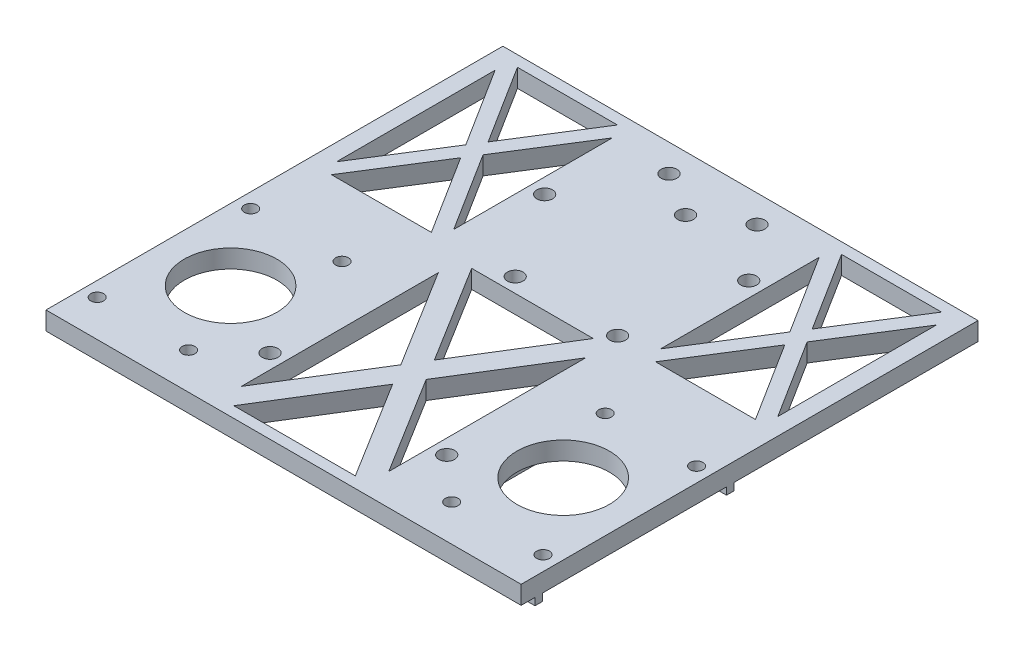
SolidWorks part; units mm, degrees
ref_plane "Front Plane" through (0, 0, 0) normal (0, 0, 1) x (1, 0, 0)
ref_plane "Top Plane" through (0, 0, 0) normal (0, 1, 0) x (1, 0, 0)
ref_plane "Right Plane" through (0, 0, 0) normal (1, 0, 0) x (0, 0, -1)
sketch "Sketch1" plane through (0, 0, 0) normal (0, 1, 0) x (1, 0, 0)
  line L1 (-65, 62.5) -> (65, 62.5)
  line L2 (-65, 62.5) -> (-65, -62.5)
  line L3 (-65, -62.5) -> (65, -62.5)
  line L4 (65, 62.5) -> (65, -62.5)
  line L5 (-65, 62.5) -> (65, -62.5) construction
  line L6 (-65, -62.5) -> (65, 62.5) construction
  point P0 (0, 0)
  dimension "D1" = 130
  dimension "D2" = 125
extrude "Boss-Extrude1" add sketch "Sketch1" along normal blind 5
sketch "Sketch2" plane through (0, 5, 0) normal (0, 1, 0) x (1, 0, 0)
  line L1 (-65, -62.5) -> (65, -62.5) construction
  line L2 (-65, 62.5) -> (-65, -62.5) construction
  circle A0 centre (-61, -52.5) radius 1.75
  circle A1 centre (-36, -52.5) radius 1.75
  circle A2 centre (-36, -10.5) radius 1.75
  circle A3 centre (-61, -10.5) radius 1.75
  circle A4 centre (-45.5, -31.5) radius 12.65
  dimension "D2" = 25.3
  dimension "D7" = 3.5
  dimension "D8" = 3.5
  dimension "D9" = 3.5
  dimension "D10" = 3.5
  dimension "D1" = 19.5
  dimension "D3" = 31
  dimension "D4" = 4
  dimension "D5" = 10
  dimension "D6" = 10
  dimension "D11" = 4
  dimension "D12" = 42
  dimension "D13" = 42
  dimension "D14" = 25
  dimension "D15" = 25
extrude "Cut-Extrude1" cut sketch "Sketch2" against normal blind 10
ref_plane "Plane1" through (0, 0, 0) normal (-1, 0, 0) x (0, 0, 1)
ref_plane "Plane2" through (0, 0, 0) normal (0, 0, 1) x (1, 0, 0)
mirror "Mirror3" about plane through (0, 0, 0) normal (-1, 0, 0) of "Cut-Extrude1"
sketch "Sketch3" plane through (0, 5, 0) normal (0, 1, 0) x (1, 0, 0)
  line L0 (-65, -62.5) -> (65, -62.5) construction
  line L1 (-65, 62.5) -> (-65, -62.5) construction
  line L2 (65, -62.5) -> (65, 62.5) construction
  line L3 (65, 62.5) -> (-65, 62.5) construction
  circle A0 centre (-24.17, -42.03) radius 2.15
  circle A1 centre (24.17, -42.03) radius 2.15
  circle A2 centre (-8.73, 9.6) radius 2.15
  circle A3 centre (19.29, 9.6) radius 2.15
  circle A4 centre (-24.17, 33.11) radius 2.15
  circle A5 centre (24.17, 40.6) radius 2.15
  dimension "D1" = 4.3
  dimension "D6" = 4.3
  dimension "D7" = 4.3
  dimension "D10" = 4.3
  dimension "D11" = 4.3
  dimension "D12" = 4.3
  dimension "D2" = 20.47
  dimension "D3" = 40.83
  dimension "D4" = 20.47
  dimension "D5" = 40.83
  dimension "D8" = 72.1
  dimension "D9" = 56.27
  dimension "D13" = 45.71
  dimension "D14" = 72.1
  dimension "D15" = 29.39
  dimension "D16" = 21.9
  dimension "D17" = 40.83
extrude "Cut-Extrude2" cut sketch "Sketch3" against normal blind 10
sketch "Sketch4" plane through (0, 5, 0) normal (0, 1, 0) x (1, 0, 0)
  line L0 (0, 62.5) -> (0, 47.5) construction
  line L1 (65, 62.5) -> (-65, 62.5) construction
  line L2 (-12.0498, 55) -> (12.0498, 55) construction
  circle A0 centre (0, 47.5) radius 2.15
  circle A1 centre (12.0498, 55) radius 2.15
  circle A2 centre (-12.0498, 55) radius 2.15
  point P9 (0, 55)
  dimension "D2" = 4.3
  dimension "D3" = 4.3
  dimension "D4" = 4.3
  dimension "D1" = 15
  dimension "D5" = 24.0996
extrude "Cut-Extrude3" cut sketch "Sketch4" against normal blind 10
sketch "Sketch5" plane through (0, 0, 0) normal (0, -1, 0) x (1, 0, 0)
  line L0 (-58.15, 31.5) -> (-65, 31.5) construction
  line L1 (-65, -62.5) -> (-65, 62.5) construction
  line L2 (-65, 56.7) -> (-65, 6.3)
  line L3 (-65, 56.7) -> (-31.6, 56.7)
  line L4 (-31.6, 56.7) -> (-31.6, 6.3)
  line L5 (-31.6, 6.3) -> (-65, 6.3)
  line L6 (-65, 58.7) -> (-29.6, 58.7)
  line L7 (-29.6, 58.7) -> (-29.6, 4.3)
  line L8 (-29.6, 4.3) -> (-65, 4.3)
  line L9 (-65, 4.3) -> (-65, 6.3)
  line L10 (-65, 58.7) -> (-65, 56.7)
  circle A0 centre (-45.5, 31.5) radius 12.65 construction
  point P10 (-65, 31.5)
  line M39 (-65, 62.5) -> (-65, -62.5)
  dimension "D1" = 50.4
  dimension "D2" = 33.4
  dimension "D3" = 2
  dimension "D4" = 2
  dimension "D5" = 2
extrude "Boss-Extrude2" add sketch "Sketch5" along normal blind 2 contours L8 L7 L6 L3 L4 L5 M39
mirror "Mirror5" about plane through (0, 0, 0) normal (-1, 0, 0) of "Boss-Extrude2"
sketch "Sketch6" plane through (0, 0, 0) normal (0, -1, 0) x (1, 0, 0)
  circle A0 centre (-12.0498, -55) radius 2.65
  circle A1 centre (12.0498, -55) radius 2.65
  circle A2 centre (0, -47.5) radius 2.65
  circle A3 centre (24.17, -40.6) radius 2.65
  circle A4 centre (-24.17, -33.11) radius 2.65
  circle A5 centre (-8.73, -9.6) radius 2.65
  circle A6 centre (19.29, -9.6) radius 2.65
  circle A7 centre (-61, 10.5) radius 2.65
  circle A8 centre (-61, 52.5) radius 2.65
  circle A9 centre (-36, 52.5) radius 2.65
  circle A10 centre (-36, 10.5) radius 2.65
  circle A11 centre (-24.17, 42.03) radius 2.65
  circle A12 centre (24.17, 42.03) radius 2.65
  circle A13 centre (36, 52.5) radius 2.65
  circle A14 centre (36, 10.5) radius 2.65
  circle A15 centre (61, 10.5) radius 2.65
  circle A16 centre (61, 52.5) radius 2.65
  dimension "D1" = 5.3
  dimension "D2" = 5.3
  dimension "D3" = 5.3
  dimension "D4" = 5.3
  dimension "D5" = 5.3
  dimension "D6" = 5.3
  dimension "D7" = 5.3
  dimension "D8" = 5.3
  dimension "D9" = 5.3
  dimension "D10" = 5.3
  dimension "D11" = 5.3
  dimension "D12" = 5.3
  dimension "D13" = 5.3
  dimension "D14" = 5.3
  dimension "D15" = 5.3
  dimension "D16" = 5.3
  dimension "D17" = 5.3
extrude "Cut-Extrude4" cut sketch "Sketch6" against normal blind 0.5
sketch "Sketch7" plane through (0, 0, 0) normal (0, -1, 0) x (1, 0, 0)
  line L0 (-65, 62.5) -> (65, 62.5) construction
  line L1 (-20.17, 59.5) -> (20.17, 59.5)
  line L2 (-20.17, 59.5) -> (-20.17, -5.6)
  line L3 (-20.17, -5.6) -> (20.17, -5.6)
  line L4 (20.17, 59.5) -> (20.17, -5.6)
  line L5 (-20.17, 59.5) -> (20.17, -5.6) construction
  line L6 (-20.17, -5.6) -> (20.17, 59.5) construction
  line L7 (-16.6299, 59.5) -> (0, 32.6629)
  line L8 (0, 32.6629) -> (16.6299, 59.5)
  line L9 (20.17, 53.9) -> (3.4701, 26.95)
  line L10 (3.4701, 26.95) -> (20.17, 0)
  line L11 (16.6299, -5.6) -> (0, 21.2371)
  line L12 (0, 21.2371) -> (-16.6299, -5.6)
  line L13 (-20.17, 0) -> (-3.4701, 26.95)
  line L14 (-3.4701, 26.95) -> (-20.17, 53.9)
  circle A0 centre (-24.17, 42.03) radius 2.65 construction
  circle A1 centre (24.17, 42.03) radius 2.65 construction
  circle A2 centre (-8.73, -9.6) radius 2.65 construction
  point P23 (0, 0)
  point P25 (0, 26.95)
  point P26 (0, 0)
  dimension "D1" = 3
  dimension "D2" = 4
  dimension "D3" = 4
  dimension "D4" = 4
extrude "Cut-Extrude5" cut sketch "Sketch7" against normal through all contours L13 L14 L2 | L7 L8 L1 | L9 L10 L4 | L11 L12 L3
sketch "Sketch8" plane through (0, 0, 0) normal (0, -1, 0) x (1, 0, 0)
  line L0 (65, -62.5) -> (-65, -62.5) construction
  line L1 (-60.3724, -8.6) -> (-28.2984, -8.6)
  line L2 (-60.3724, -8.6) -> (-60.3724, -59.5)
  line L3 (-60.3724, -59.5) -> (-28.2984, -59.5)
  line L4 (-28.2984, -8.6) -> (-28.2984, -59.5)
  line L9 (-16.6299, -5.6) -> (16.6299, -5.6) construction
  line L10 (-60.3724, -8.6) -> (-28.2984, -59.5) construction
  line L11 (-60.3724, -59.5) -> (-28.2984, -8.6) construction
  line L12 (0, -5.6) -> (0, -62.5) construction
  line L13 (60.3724, -59.5) -> (28.2984, -8.6) construction
  line L14 (-58.0084, -8.6) -> (-44.3354, -30.2985)
  line L15 (-44.3354, -30.2985) -> (-30.6623, -8.6)
  line L16 (-28.2984, -12.3515) -> (-41.9714, -34.05)
  line L17 (-41.9714, -34.05) -> (-28.2984, -55.7485)
  line L18 (-30.6623, -59.5) -> (-44.3354, -37.8015)
  line L19 (-44.3354, -37.8015) -> (-58.0084, -59.5)
  line L20 (-60.3724, -55.7485) -> (-46.6993, -34.05)
  line L21 (-46.6993, -34.05) -> (-60.3724, -12.3515)
  line L22 (60.3724, -8.6) -> (28.2984, -59.5) construction
  line L23 (46.6993, -34.05) -> (60.3724, -12.3515)
  line L24 (60.3724, -55.7485) -> (46.6993, -34.05)
  line L25 (44.3354, -37.8015) -> (58.0084, -59.5)
  line L26 (30.6623, -59.5) -> (44.3354, -37.8015)
  line L27 (41.9714, -34.05) -> (28.2984, -55.7485)
  line L28 (28.2984, -12.3515) -> (41.9714, -34.05)
  line L29 (44.3354, -30.2985) -> (30.6623, -8.6)
  line L30 (58.0084, -8.6) -> (44.3354, -30.2985)
  line L31 (28.2984, -8.6) -> (28.2984, -59.5)
  line L32 (60.3724, -59.5) -> (28.2984, -59.5)
  line L33 (60.3724, -8.6) -> (60.3724, -59.5)
  line L34 (60.3724, -8.6) -> (28.2984, -8.6)
  point P41 (-44.3354, -34.05)
  dimension "D1" = 2
  dimension "D2" = 3
  dimension "D3" = 3
  dimension "D4" = 2
  dimension "D5" = 2
  dimension "D6" = 2
extrude "Cut-Extrude6" cut sketch "Sketch8" against normal through all contours L20 L21 L2 | L14 L15 L1 | L16 L17 L4 | L18 L19 L3 | L28 L31 L27 | L30 L34 L29 | L33 L23 L24 | L32 L25 L26
